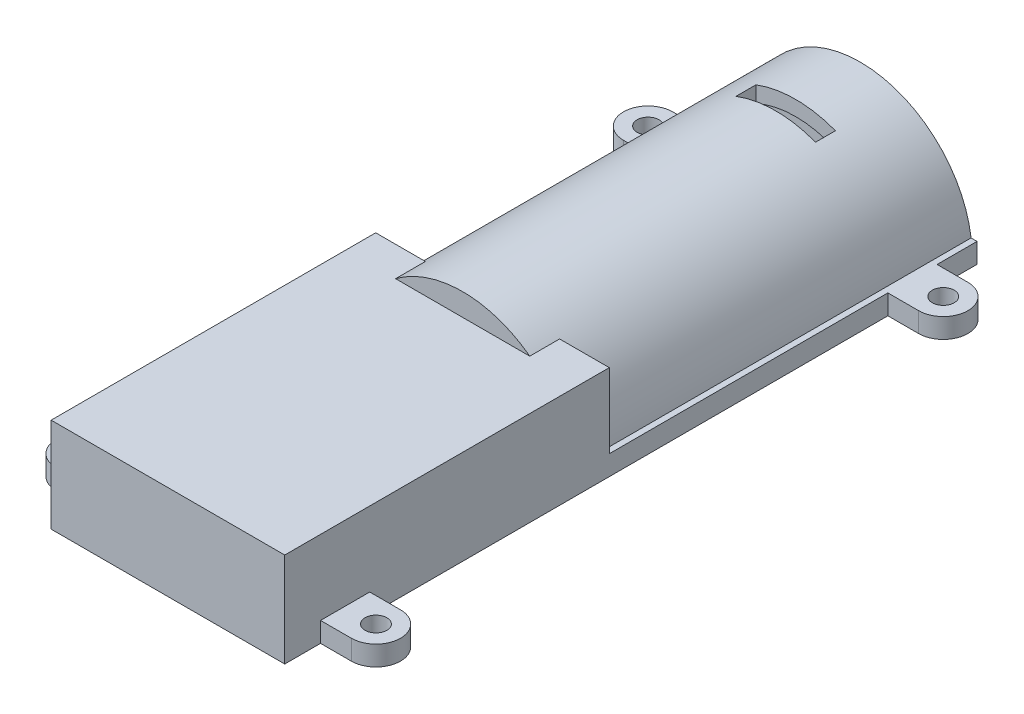
SolidWorks part; units mm, degrees
material "ABS"
ref_plane "Front Plane" through (0, 0, 0) normal (0, 0, 1) x (1, 0, 0)
ref_plane "Top Plane" through (0, 0, 0) normal (0, 1, 0) x (1, 0, 0)
ref_plane "Right Plane" through (0, 0, 0) normal (1, 0, 0) x (0, 0, -1)
sketch "Sketch1" plane through (0, 0, 0) normal (0, 1, 0) x (1, 0, 0)
  line L0 (71.0303, 18.0809) -> (64.8303, 18.0809)
  line L1 (64.8303, 18.0809) -> (64.8303, 27.9809)
  line L2 (64.8303, 27.9809) -> (71.0303, 27.9809)
  line L3 (11.6303, 18.0809) -> (17.8303, 18.0809)
  line L4 (17.8303, 18.0809) -> (17.8303, 27.9809)
  line L5 (17.8303, 27.9809) -> (11.6303, 27.9809)
  line L6 (64.8303, -96.0691) -> (71.0303, -96.0691)
  line L7 (71.0303, -86.1691) -> (64.8303, -86.1691)
  line L8 (64.8303, -86.1691) -> (64.8303, -96.0691)
  line L9 (11.6303, -96.0691) -> (17.8303, -96.0691)
  line L10 (17.8303, -96.0691) -> (17.8303, -86.1691)
  line L11 (17.8303, -86.1691) -> (11.6303, -86.1691)
  line L13 (17.8303, -103.2691) -> (64.8303, -103.2691)
  line L14 (17.8303, -103.2691) -> (17.8303, 36.0309)
  line L15 (17.8303, 36.0309) -> (64.8303, 36.0309)
  line L16 (64.8303, -103.2691) -> (64.8303, 36.0309)
  circle A0 centre (71.0303, -91.1191) radius 2.2
  circle A1 centre (71.0303, -91.1191) radius 4.95
  circle A2 centre (11.6303, -91.1191) radius 2.2
  circle A3 centre (11.6303, -91.1191) radius 4.95
  circle A4 centre (11.6303, 23.0309) radius 2.2
  circle A5 centre (71.0303, 23.0309) radius 2.2
  circle A6 centre (71.0303, 23.0309) radius 4.95
  circle A7 centre (11.6303, 23.0309) radius 4.95
  dimension "D1" = 4.4
  dimension "D2" = 4.4
  dimension "D3" = 4.4
  dimension "D4" = 4.4
  dimension "D13" = 9.9
  dimension "D15" = 9.9
  dimension "D18" = 9.9
  dimension "D20" = 9.9
  dimension "D5" = 59.4
  dimension "D6" = 59.4
  dimension "D7" = 23.0309
  dimension "D8" = 114.15
  dimension "D9" = 11.6303
  dimension "D10" = 23.0309
  dimension "D11" = 11.6303
  dimension "D12" = 91.1191
  dimension "D14" = 6.2
  dimension "D16" = 6.2
  dimension "D17" = 9.9
  dimension "D19" = 6.2
  dimension "D21" = 6.2
  dimension "D22" = 6.2
  dimension "D23" = 139.3
  dimension "D24" = 47
  dimension "D25" = 13
  dimension "D26" = 0
extrude "Boss-Extrude1" add sketch "Sketch1" along normal blind 4 contours A7 A4 | A7 L3 L4 L5 | L13 L16 L8 L1 L15 L14 L4 L10 | A6 A5 | A6 L2 L1 L0 | A1 L7 L8 L6 | A1 A0 | A3 L9 L10 L11 | A3 A2
sketch "Sketch2" plane through (0, 4, 0) normal (0, 1, 0) x (1, 0, 0)
  line L1 (17.8303, 36.0309) -> (64.8303, 36.0309)
  line L2 (17.8303, 36.0309) -> (17.8303, -103.2691)
  line L3 (17.8303, -103.2691) -> (64.8303, -103.2691)
  line L4 (64.8303, 36.0309) -> (64.8303, -103.2691)
extrude "Boss-Extrude2" add sketch "Sketch2" along normal blind 19.5
sketch "Sketch3" plane through (0, 0, 0) normal (0, -1, 0) x (1, 0, 0)
  line L0 (17.8303, 103.2691) -> (64.8303, 103.2691) construction
  line L1 (61.8303, 100.2691) -> (20.8303, 100.2691)
  line L2 (61.8303, 100.2691) -> (61.8303, 40.9691)
  line L3 (61.8303, 40.9691) -> (20.8303, 40.9691)
  line L4 (20.8303, 100.2691) -> (20.8303, 40.9691)
  line L5 (64.8303, 86.1691) -> (64.8303, -18.0809) construction
  line L6 (17.8303, 86.1691) -> (17.8303, -18.0809) construction
  dimension "D1" = 3
  dimension "D2" = 3
  dimension "D3" = 3
  dimension "D4" = 59.3
extrude "Cut-Extrude1" cut sketch "Sketch3" against normal blind 16 contours L2 L1 L4 L3
sketch "Sketch6" plane through (0, 0, -36.0309) normal (0, 0, -1) x (-1, 0, 0)
  line L0 (-17.8303, 0) -> (-64.8303, 0) construction
  line L1 (-41.3303, 23.5) -> (-41.3303, 0) construction
  line L2 (-64.8303, 23.5) -> (-17.8303, 23.5) construction
  circle A0 centre (-41.3303, 1) radius 19.5
  dimension "D1" = 39
  dimension "D2" = 1
extrude "Cut-Extrude3" cut sketch "Sketch6" against normal blind 76 from offset 3 offset against normal yes
sketch "Sketch7" plane through (0, 0, -36.0309) normal (0, 0, -1) x (-1, 0, 0)
  line L0 (-41.3303, 23.5) -> (-41.3303, 0) construction
  line L1 (-64.8303, 23.5) -> (-17.8303, 23.5) construction
  line L2 (-17.8303, 0) -> (-64.8303, 0) construction
  line L3 (-64.8303, 4) -> (-63.6294, 4)
  line L4 (-64.8303, 23.5) -> (-64.8303, 4)
  line L5 (-17.8303, 23.5) -> (-64.8303, 23.5)
  line L6 (-17.8303, 4) -> (-19.0312, 4)
  line L7 (-17.8303, 23.5) -> (-17.8303, 4)
  circle A0 centre (-41.3303, 1) radius 22.5
  line M3 (-17.8303, 0) -> (-17.8303, 23.5)
  line M4 (-17.8303, 23.5) -> (-64.8303, 23.5)
  line M5 (-64.8303, 23.5) -> (-64.8303, 0)
  dimension "D1" = 45
  dimension "D2" = 1
extrude "Cut-Extrude4" cut sketch "Sketch7" against normal blind 74 contours A0 L5 L3 M5 | A0 L6 M3 M4
sketch "Sketch9" plane through (0, 0, 37.9691) normal (0, 0, -1) x (-1, 0, 0)
  line L0 (-17.8303, 4) -> (-17.8303, 23.5) construction
  line L1 (-17.8303, 19) -> (-64.8303, 19)
  line L2 (-17.8303, 19) -> (-17.8303, 23.5)
  line L3 (-17.8303, 23.5) -> (-64.8303, 23.5)
  line L4 (-64.8303, 19) -> (-64.8303, 23.5)
  line L5 (-17.8303, 4) -> (-19.0312, 4) construction
  circle A0 centre (-41.3303, 1) radius 22.5
  arc M1 (-63.6294, 4) -> (-41.3303, 23.5) centre (-41.3303, 1) cw
  line M2 (-41.3303, 23.5) -> (-64.8303, 23.5)
  line M3 (-64.8303, 23.5) -> (-64.8303, 4)
  dimension "D1" = 4.5
  dimension "D2" = 47
  dimension "D3" = 47
  dimension "D4" = 19.5
extrude "Cut-Extrude6" cut sketch "Sketch9" against normal up to next contours L1 M1 M2 M3 | A0 L1 L2 L3
sketch "Sketch10" plane through (0, 4, 0) normal (0, 1, 0) x (1, 0, 0)
  line L0 (41.3303, -37.9691) -> (41.3303, 36.0309) construction
  line L1 (49.3303, 23.0309) -> (33.3303, 23.0309)
  line L2 (49.3303, 23.0309) -> (49.3303, 19.0309)
  line L3 (49.3303, 19.0309) -> (33.3303, 19.0309)
  line L4 (33.3303, 23.0309) -> (33.3303, 19.0309)
  line L5 (63.6294, 36.0309) -> (19.0312, 36.0309) construction
  dimension "D1" = 4
  dimension "D2" = 16
  dimension "D3" = 8
  dimension "D4" = 13
extrude "Cut-Extrude7" cut sketch "Sketch10" against normal through all both and the other way through all
sketch "Sketch12" plane through (0, 19, 0) normal (0, 1, 0) x (1, 0, 0)
  line L0 (64.8303, -103.2691) -> (64.8303, -37.9691) construction
  line L1 (17.8303, -103.2691) -> (64.8303, -103.2691)
  line L2 (17.8303, -103.2691) -> (17.8303, -43.9691)
  line L3 (17.8303, -43.9691) -> (64.8303, -43.9691)
  line L4 (64.8303, -103.2691) -> (64.8303, -43.9691)
  line L5 (17.8303, -37.9691) -> (27.8303, -37.9691) construction
  dimension "D1" = 6
extrude "Cut-Extrude8" cut sketch "Sketch12" along normal through all
